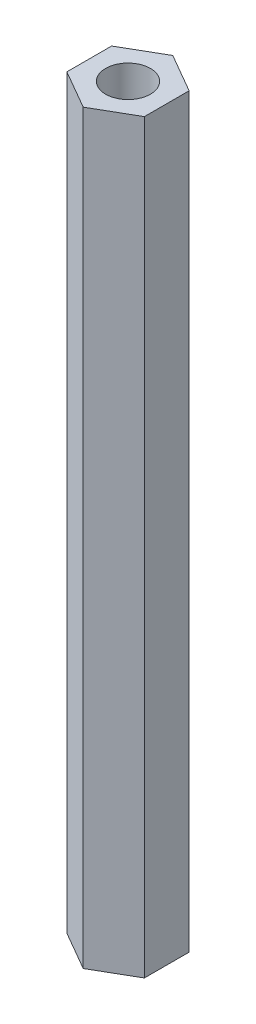
SolidWorks part; units mm, degrees
material "Brass"
ref_plane "Front Plane" through (0, 0, 0) normal (0, 0, 1) x (1, 0, 0)
ref_plane "Top Plane" through (0, 0, 0) normal (0, 1, 0) x (1, 0, 0)
ref_plane "Right Plane" through (0, 0, 0) normal (1, 0, 0) x (0, 0, -1)
sketch "Sketch1" plane through (0, 0, 0) normal (0, 1, 0) x (1, 0, 0)
  line L1 (0, -3) -> (2.5981, -1.5)
  line L2 (2.5981, -1.5) -> (2.5981, 1.5)
  line L3 (2.5981, 1.5) -> (0, 3)
  line L4 (0, 3) -> (-2.5981, 1.5)
  line L5 (-2.5981, 1.5) -> (-2.5981, -1.5)
  line L6 (-2.5981, -1.5) -> (0, -3)
  circle A0 centre (0, 0) radius 2 construction
  circle A1 centre (0, 0) radius 3 construction
  dimension "D1" = 4
  dimension "D2" = 6
extrude "Boss-Extrude1" add sketch "Sketch1" along normal blind 50
sketch "Sketch2" plane through (0, 50, 0) normal (0, 1, 0) x (1, 0, 0)
  circle A0 centre (0, 0) radius 1.5
  dimension "D1" = 3
extrude "Cut-Extrude1" cut sketch "Sketch2" against normal through all
